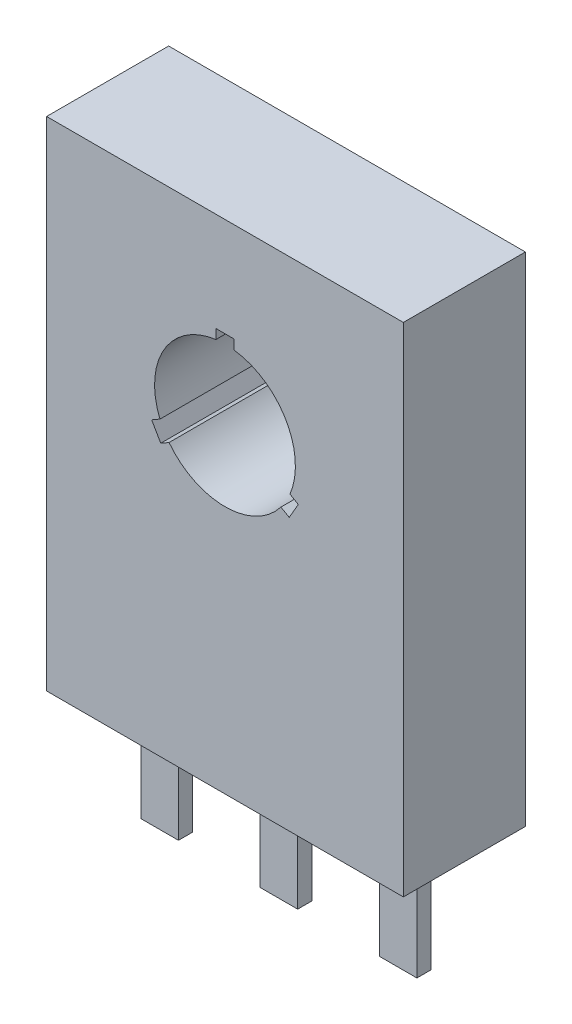
SolidWorks part; units mm, degrees
ref_plane "Plano frontal" through (0, 0, 0) normal (0, 0, 1) x (1, 0, 0)
ref_plane "Plano superior" through (0, 0, 0) normal (0, 1, 0) x (1, 0, 0)
ref_plane "Plano direito" through (0, 0, 0) normal (1, 0, 0) x (0, 0, -1)
sketch "Esboço1" plane through (0, 0, 0) normal (0, 0, 1) x (1, 0, 0)
  line L1 (-3.8, -5.3) -> (3.8, -5.3)
  line L2 (-3.8, -5.3) -> (-3.8, 5.3)
  line L3 (-3.8, 5.3) -> (3.8, 5.3)
  line L4 (3.8, -5.3) -> (3.8, 5.3)
  line L5 (-3.8, -5.3) -> (3.8, 5.3) construction
  line L6 (-3.8, 5.3) -> (3.8, -5.3) construction
  circle A0 centre (0, 1.5) radius 1.5
  point P0 (0, 0)
  dimension "D3" = 3
  dimension "D1" = 7.6
  dimension "D2" = 10.6
  dimension "D4" = 3.8
extrude "Ressalto-extrusão1" add sketch "Esboço1" along normal blind 2.6
sketch "Esboço2" plane through (0, 0, 2.6) normal (0, 0, 1) x (1, 0, 0)
  line L1 (-0.1935, 2.0501) -> (0.1935, 2.0501)
  line L2 (-0.1935, 2.0501) -> (-0.1935, 3.1917)
  line L3 (-0.1935, 3.1917) -> (0.1935, 3.1917)
  line L4 (0.1935, 2.0501) -> (0.1935, 3.1917)
  line L5 (-0.1935, 2.0501) -> (0.1935, 3.1917) construction
  line L6 (-0.1935, 3.1917) -> (0.1935, 2.0501) construction
  point P0 (0, 2.6209)
extrude "Corte-extrusão1" cut sketch "Esboço2" against normal blind 2.4
pattern_circular "PadrãoCircular1" count 3 over 360 about axis through (0, 1.5, 0) along (0, 0, 1) of "Corte-extrusão1"
sketch "Esboço3" plane through (0, 0, 0) normal (0, 0, -1) x (-1, 0, 0)
  line L0 (-3.8, 5.3) -> (3.8, 5.3) construction
  line L1 (-1.7, -3.5) -> (1.7, -3.5)
  line L2 (-2.7, -2.5) -> (-2.7, 3)
  line L3 (-1.7, 4) -> (1.7, 4)
  line L4 (2.7, -2.5) -> (2.7, 3)
  line L5 (-2.7, -3.5) -> (2.7, 4) construction
  line L6 (-2.7, 4) -> (2.7, -3.5) construction
  arc A0 (-1.7, -3.5) -> (-2.7, -2.5) centre (-1.7, -2.5) cw
  arc A1 (1.7, -3.5) -> (2.7, -2.5) centre (1.7, -2.5) ccw
  arc A2 (1.7, 4) -> (2.7, 3) centre (1.7, 3) cw
  arc A3 (-2.7, 3) -> (-1.7, 4) centre (-1.7, 3) cw
  point P0 (0, 0.25)
  dimension "D5" = 1
  dimension "D1" = 5.4
  dimension "D2" = 0
  dimension "D3" = 1.3
  dimension "D4" = 7.5
extrude "Corte-extrusão2" cut sketch "Esboço3" against normal blind 0.05
sketch "Esboço4" plane through (0, -5.3, 0) normal (0, -1, 0) x (1, 0, 0)
  line L1 (-2.94, 1.1488) -> (-2.14, 1.1488)
  line L2 (-2.94, 1.1488) -> (-2.94, 1.4512)
  line L3 (-2.94, 1.4512) -> (-2.14, 1.4512)
  line L4 (-2.14, 1.1488) -> (-2.14, 1.4512)
  line L5 (-2.94, 1.1488) -> (-2.14, 1.4512) construction
  line L6 (-2.94, 1.4512) -> (-2.14, 1.1488) construction
  line L7 (-0.4, 1.1488) -> (0.4, 1.1488)
  line L8 (-0.4, 1.1488) -> (-0.4, 1.4512)
  line L9 (-0.4, 1.4512) -> (0.4, 1.4512)
  line L10 (0.4, 1.1488) -> (0.4, 1.4512)
  line L11 (-0.4, 1.1488) -> (0.4, 1.4512) construction
  line L12 (-0.4, 1.4512) -> (0.4, 1.1488) construction
  line L13 (2.14, 1.1488) -> (2.94, 1.1488)
  line L14 (2.14, 1.1488) -> (2.14, 1.4512)
  line L15 (2.14, 1.4512) -> (2.94, 1.4512)
  line L16 (2.94, 1.1488) -> (2.94, 1.4512)
  line L17 (2.14, 1.1488) -> (2.94, 1.4512) construction
  line L18 (2.14, 1.4512) -> (2.94, 1.1488) construction
  point P0 (-2.54, 1.3)
  point P5 (0, 1.3)
  point P10 (2.54, 1.3)
  dimension "D1" = 2.54
  dimension "D2" = 2.54
  dimension "D3" = 0.8
  dimension "D4" = 0.8
  dimension "D5" = 0.8
  dimension "D6" = 0
extrude "Ressalto-extrusão2" add sketch "Esboço4" along normal blind 2.5
